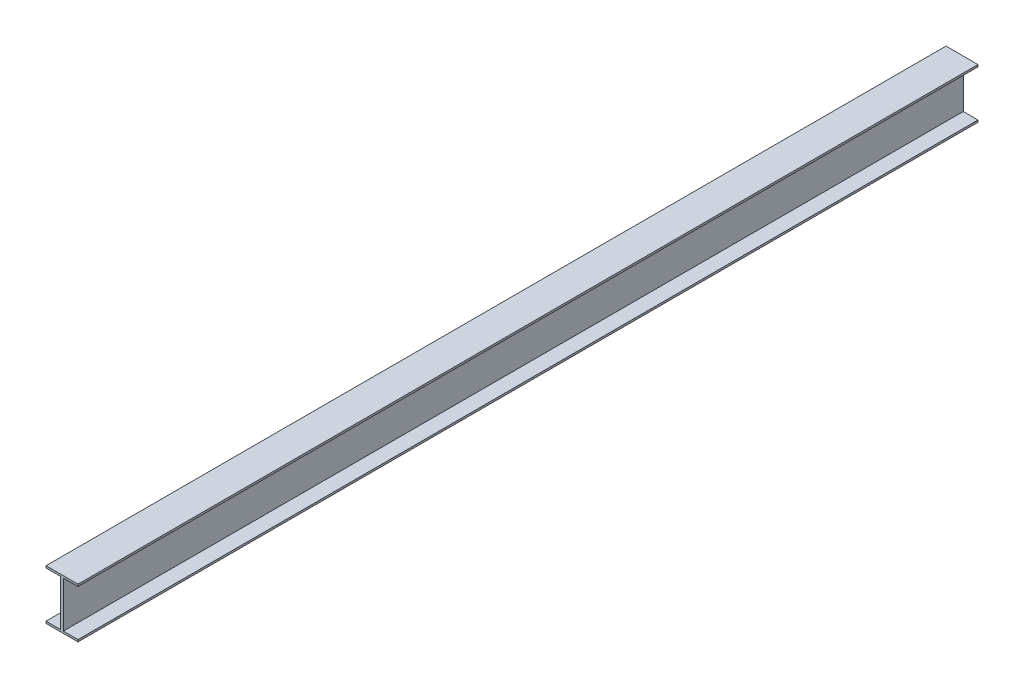
SolidWorks part; units mm, degrees
ref_plane "前视基准面" through (0, 0, 0) normal (0, 0, 1) x (1, 0, 0)
ref_plane "上视基准面" through (0, 0, 0) normal (0, 1, 0) x (1, 0, 0)
ref_plane "右视基准面" through (0, 0, 0) normal (1, 0, 0) x (0, 0, -1)
sketch "草图2" plane through (0, 0, 0) normal (0, 0, 1) x (1, 0, 0)
  line L1 (0, 0) -> (160, 0)
  line L2 (0, 0) -> (0, 250)
  line L3 (0, 250) -> (160, 250)
  line L4 (160, 0) -> (160, 250)
  dimension "D1" = 160
  dimension "D2" = 250
extrude "凸台-拉伸1" add sketch "草图2" along normal blind 4500
sketch "草图3" plane through (0, 0, 4500) normal (0, 0, 1) x (1, 0, 0)
  line L0 (80, -750) -> (80, 49250) construction
  line L1 (160, 250) -> (0, 250) construction
  line L2 (160, 0) -> (160, 250) construction
  line L3 (160, 240) -> (86.5, 240)
  line L4 (160, 240) -> (160, 10)
  line L5 (160, 10) -> (86.5, 10)
  line L6 (86.5, 240) -> (86.5, 10)
  line L7 (0, 250) -> (0, 0) construction
  line L8 (0, 240) -> (73.5, 240)
  line L9 (0, 240) -> (0, 10)
  line L10 (0, 10) -> (73.5, 10)
  line L11 (73.5, 240) -> (73.5, 10)
  line L12 (-840, 125) -> (49160, 125) construction
  point P5 (80, 250)
  point P20 (160, 125)
  dimension "D1" = 10
  dimension "D2" = 13
extrude "切除-拉伸1" cut sketch "草图3" against normal through all
